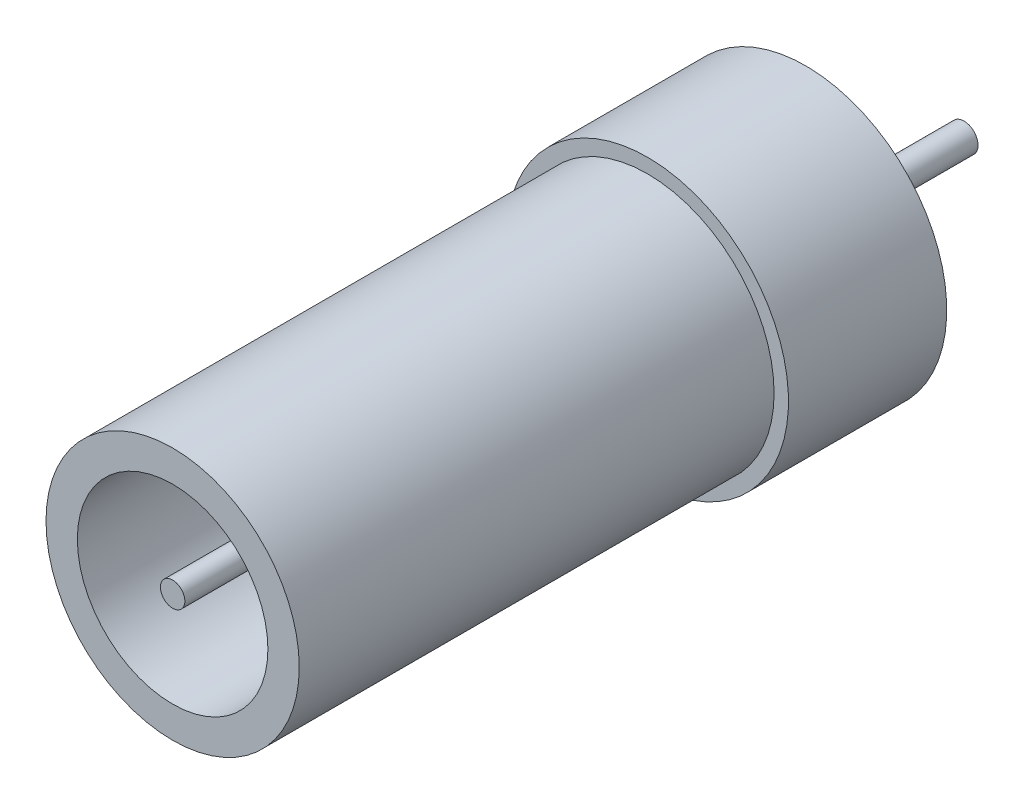
SolidWorks part; units mm, degrees
ref_plane "Front Plane" through (0, 0, 0) normal (0, 0, 1) x (1, 0, 0)
ref_plane "Top Plane" through (0, 0, 0) normal (0, 1, 0) x (1, 0, 0)
ref_plane "Right Plane" through (0, 0, 0) normal (1, 0, 0) x (0, 0, -1)
sketch "Sketch1" plane through (0, 0, 0) normal (0, 0, 1) x (1, 0, 0)
  circle A0 centre (0, 0) radius 4
  circle A1 centre (0, 0) radius 3
extrude "Boss-Extrude1" add sketch "Sketch1" along normal blind 15
sketch "Sketch2" plane through (0, 0, 0) normal (0, 0, -1) x (-1, 0, 0)
  circle A0 centre (0, 0) radius 3
  circle A1 centre (0, 0) radius 0.3883
extrude "Boss-Extrude3" add sketch "Sketch2" against normal blind 15 contours A0
sketch "Sketch3" plane through (0, 0, 15) normal (0, 0, 1) x (1, 0, 0)
  circle A0 centre (0, 0) radius 0.3863
  circle A1 centre (0, 0) radius 3.0098
extrude "Cut-Extrude2" cut sketch "Sketch3" against normal blind 13
sketch "Sketch4" plane through (0, 0, 0) normal (0, 0, -1) x (-1, 0, 0)
  circle A0 centre (0, 0) radius 4.4541
extrude "Boss-Extrude4" add sketch "Sketch4" along normal blind 5
sketch "Sketch5" plane through (0, 0, -5) normal (0, 0, -1) x (-1, 0, 0)
  circle A0 centre (0, 0) radius 0.4424
extrude "Boss-Extrude5" add sketch "Sketch5" along normal blind 5
